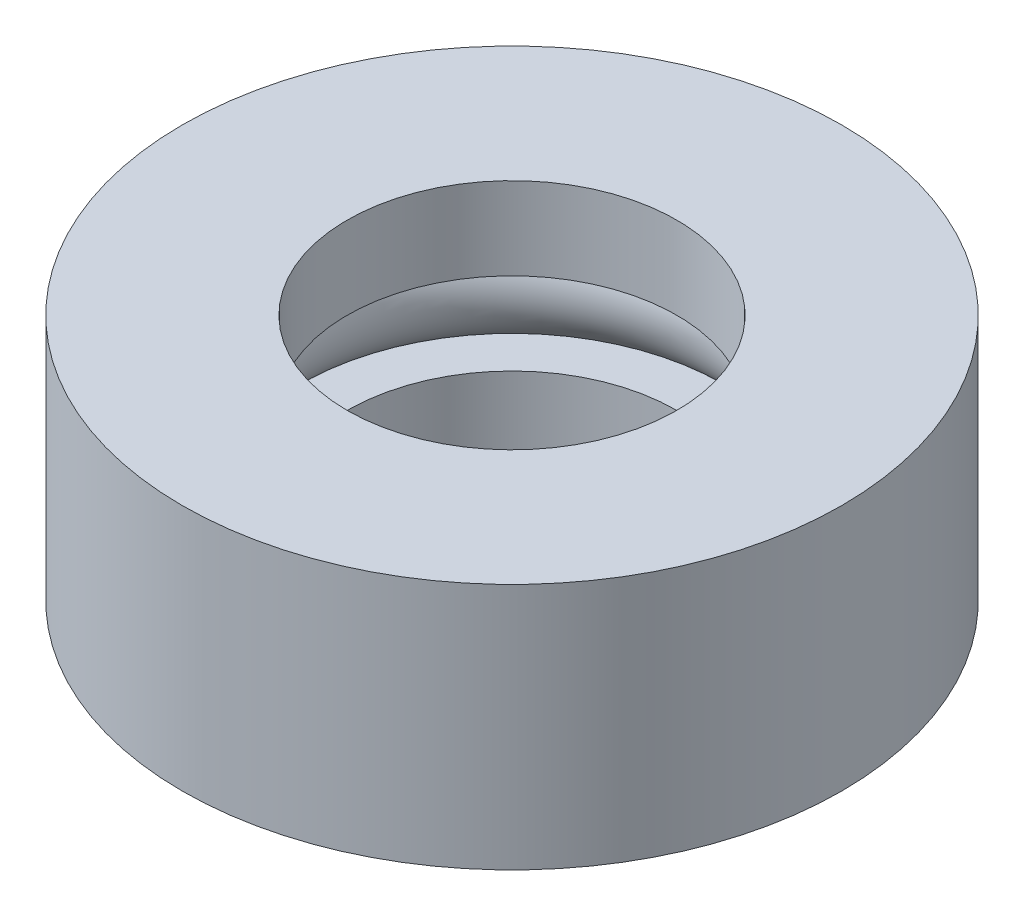
SolidWorks part; units mm, degrees
ref_plane "正面" through (0, 0, 0) normal (0, 0, 1) x (1, 0, 0)
ref_plane "平面" through (0, 0, 0) normal (0, 1, 0) x (1, 0, 0)
ref_plane "右側面" through (0, 0, 0) normal (1, 0, 0) x (0, 0, -1)
sketch "ｽｹｯﾁ3" plane through (0, 0, 0) normal (1, 0, 0) x (0, 0, -1)
  line L0 (-4.5, 0) -> (0, 0) construction
  line L1 (0, 7.9934) -> (0, 0) construction
  circle A0 centre (-4.5, 0) radius 1
  dimension "D2" = 2
  dimension "D1" = 4.5
revolve "回転3" add sketch "ｽｹｯﾁ3" angle 360 about L1
ref_plane "平面1" through (0, 0.75, 0) normal (0, 1, 0) x (1, 0, 0)
sketch "ｽｹｯﾁ5" plane through (0, 0.75, 0) normal (0, 1, 0) x (1, 0, 0)
  circle A0 centre (0, 0) radius 6
  circle A1 centre (0, 0) radius 3
  dimension "D1" = 12
  dimension "D2" = 6
extrude "ﾎﾞｽ - 押し出し1" add sketch "ｽｹｯﾁ5" along normal blind 1.5 separate body
sketch "ｽｹｯﾁ6" plane through (0, 0.75, 0) normal (0, -1, 0) x (1, 0, 0)
  circle A0 centre (0, 0) radius 6
  circle A1 centre (0, 0) radius 5.25
  circle A2 centre (0, 0) radius 6 construction
  dimension "D1" = 0.75
extrude "ﾎﾞｽ - 押し出し3" add sketch "ｽｹｯﾁ6" along normal blind 1.5
sketch "ｽｹｯﾁ7" plane through (0, -0.75, 0) normal (0, -1, 0) x (1, 0, 0)
  circle A0 centre (0, 0) radius 6
  circle A3 centre (0, 0) radius 6 construction
  circle A4 centre (0, 0) radius 3
  circle A5 centre (0, 0) radius 3 construction
extrude "ﾎﾞｽ - 押し出し4" add sketch "ｽｹｯﾁ7" along normal blind 1.5
